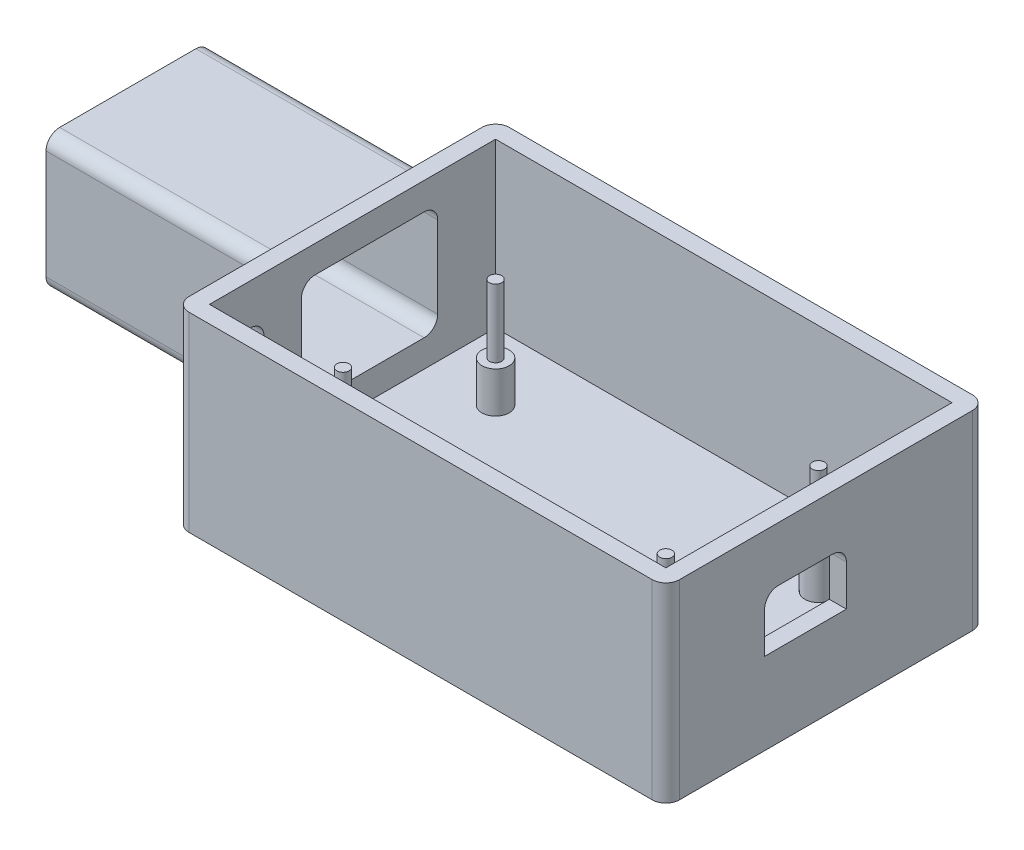
SolidWorks part; units mm, degrees
ref_plane "Front Plane" through (0, 0, 0) normal (0, 0, 1) x (1, 0, 0)
ref_plane "Top Plane" through (0, 0, 0) normal (0, 1, 0) x (1, 0, 0)
ref_plane "Right Plane" through (0, 0, 0) normal (1, 0, 0) x (0, 0, -1)
sketch "Sketch1" plane through (0, 0, 0) normal (0, 1, 0) x (1, 0, 0)
  line L0 (-10.5, -10.5) -> (-10.5, 36.5)
  line L1 (0, 0) -> (51, 0) construction
  line L2 (0, 0) -> (0, 26) construction
  line L3 (0, 26) -> (51, 26) construction
  line L4 (51, 0) -> (51, 26) construction
  line L5 (-10.5, 36.5) -> (61.5, 36.5)
  line L6 (61.5, -10.5) -> (61.5, 36.5)
  line L7 (-10.5, -10.5) -> (61.5, -10.5)
  line L8 (25.5, 36.5) -> (25.5, -10.5) construction
  line L9 (-10.5, 13) -> (61.5, 13) construction
  dimension "D1" = 51
  dimension "D2" = 26
  dimension "D3" = 10.5
extrude "Boss-Extrude1" add sketch "Sketch1" along normal blind 4
sketch "Sketch2" plane through (0, 4, 0) normal (0, 1, 0) x (1, 0, 0)
  line L0 (0, 13) -> (51, 13) construction
  line L1 (25.5, 26) -> (25.5, 0) construction
  line L8 (0, 26) -> (0, 0)
  line L9 (51, 26) -> (0, 26)
  line L10 (51, 0) -> (51, 26)
  line L11 (0, 0) -> (51, 0)
  line L12 (0, 26) -> (0, 0) construction
  line L13 (51, 26) -> (0, 26) construction
  line L14 (51, 0) -> (51, 26) construction
  line L15 (0, 0) -> (51, 0) construction
  circle A4 centre (1.8, 24.2) radius 0.9
  circle A5 centre (1.8, 1.8) radius 0.9
  circle A6 centre (49.2, 1.8) radius 0.9
  circle A7 centre (49.2, 24.2) radius 0.9
  dimension "D2" = 1.8
  dimension "D3" = 1.8
  dimension "D4" = 1.8
  dimension "D1" = 10.5
sketch "Sketch3" plane through (0, 4, 0) normal (0, 1, 0) x (1, 0, 0)
  line L0 (61.5, -10.5) -> (61.5, 36.5) construction
  line L1 (-10.5, -10.5) -> (61.5, -10.5) construction
  line L2 (61.5, 36.5) -> (-10.5, 36.5) construction
  line L3 (-10.5, 36.5) -> (-10.5, -10.5) construction
  line L4 (61.5, -10.5) -> (61.5, 36.5)
  line L5 (-10.5, -10.5) -> (61.5, -10.5)
  line L6 (61.5, 36.5) -> (-10.5, 36.5)
  line L7 (-10.5, 36.5) -> (-10.5, -10.5)
  line L8 (59, -8) -> (59, 34)
  line L9 (59, 34) -> (-8, 34)
  line L10 (-8, 34) -> (-8, -8)
  line L11 (-8, -8) -> (59, -8)
  dimension "D1" = 2.5
extrude "Boss-Extrude3" add sketch "Sketch3" along normal blind 24
extrude "Boss-Extrude4" add sketch "Sketch2" along normal blind 16
sketch "Sketch4" plane through (0, 4, 0) normal (0, 1, 0) x (1, 0, 0)
  line L0 (25.5, 34) -> (25.5, -8) construction
  line L1 (59, 34) -> (-8, 34) construction
  line L2 (-8, -8) -> (59, -8) construction
  line L3 (-8, 13) -> (59, 13) construction
  line L4 (-8, 34) -> (-8, -8) construction
  line L5 (59, -8) -> (59, 34) construction
  circle A0 centre (1.8, 24.2) radius 2
  circle A1 centre (1.8, 1.8) radius 2
  circle A2 centre (49.2, 1.8) radius 2
  circle A3 centre (49.2, 24.2) radius 2
  dimension "D1" = 4
extrude "Boss-Extrude5" add sketch "Sketch4" along normal blind 6
sketch "Sketch5" plane through (61.5, 0, 0) normal (1, 0, 0) x (0, 0, -1)
  line L1 (-8, 28) -> (-8, 4) construction
  line L7 (4, 20) -> (16, 20)
  line L8 (4, 20) -> (4, 12)
  line L9 (4, 12) -> (16, 12)
  line L10 (16, 20) -> (16, 12)
  line L11 (-8, 4) -> (34, 4) construction
  line L12 (-8, 28) -> (-8, 4) construction
  line L13 (-8, 4) -> (34, 4) construction
  dimension "D1" = 8
  dimension "D2" = 12
  dimension "D3" = 8
  dimension "D4" = 12
extrude "Cut-Extrude1" cut sketch "Sketch5" against normal blind 6
fillet "Fillet2" radius 2 4 edges at (-10.5, 14, 10.5) (-10.5, 14, -36.5) (61.5, 14, -36.5) (61.5, 14, 10.5)
fillet "Fillet3" radius 2 2 edges at (60.25, 20, -4) (60.25, 20, -16)
sketch "Sketch6" plane through (0, 0, 10.5) normal (0, 0, 1) x (1, 0, 0)
  line L0 (-8, 4) -> (59, 4) construction
  line L1 (59, 28) -> (59, 4) construction
  line L2 (-8, 4) -> (59, 4) construction
  line L3 (59, 28) -> (59, 4) construction
  line L5 (28, 24) -> (44, 24)
  line L6 (28, 24) -> (28, 15)
  line L7 (28, 15) -> (44, 15)
  line L8 (44, 24) -> (44, 15)
  dimension "D1" = 16
  dimension "D2" = 9
  dimension "D3" = 15
  dimension "D4" = 11
extrude "Cut-Extrude2" [suppressed] cut sketch "Sketch6" against normal blind 6 contours L7 L8 L5 L6
sketch "Sketch8" [suppressed] plane through (-10.5, 0, 0) normal (-1, 0, 0) x (0, 0, 1)
  line L0 (-34.5, 28) -> (-34.5, 0) construction
  line L1 (-22.5, 20) -> (-10.5, 20)
  line L2 (-22.5, 20) -> (-22.5, 12)
  line L3 (-22.5, 12) -> (-10.5, 12)
  line L4 (-10.5, 20) -> (-10.5, 12)
  line L6 (-34, 4) -> (8, 4) construction
  line L7 (-34, 4) -> (8, 4) construction
  dimension "D1" = 12
  dimension "D2" = 8
  dimension "D3" = 8
  dimension "D4" = 12
sketch "Sketch11" plane through (-10.5, 0, 0) normal (-1, 0, 0) x (0, 0, 1)
  line L0 (-34.5, 28) -> (8.5, 28) construction
  line L1 (-27.5, 26) -> (-3.5, 26)
  line L2 (-27.5, 26) -> (-27.5, 6)
  line L3 (-27.5, 6) -> (-3.5, 6)
  line L4 (-3.5, 26) -> (-3.5, 6)
  line L5 (-34.5, 28) -> (-34.5, 0) construction
  dimension "D1" = 24
  dimension "D2" = 20
  dimension "D3" = 2
  dimension "D4" = 7
extrude "Boss-Extrude7" add sketch "Sketch11" along normal blind 33
sketch "Sketch12" plane through (-8, 0, 0) normal (1, 0, 0) x (0, 0, -1)
  line L0 (27.5, 6) -> (3.5, 6) construction
  line L1 (3.5, 26) -> (27.5, 26) construction
  line L2 (3.5, 6) -> (3.5, 26) construction
  line L3 (27.5, 26) -> (27.5, 6) construction
  line L4 (27.5, 6) -> (3.5, 6) construction
  line L5 (3.5, 26) -> (27.5, 26) construction
  line L6 (3.5, 6) -> (3.5, 26) construction
  line L7 (27.5, 26) -> (27.5, 6) construction
  line L8 (5.5, 8) -> (5.5, 24)
  line L9 (5.5, 24) -> (25.5, 24)
  line L10 (25.5, 24) -> (25.5, 8)
  line L11 (25.5, 8) -> (5.5, 8)
  dimension "D1" = 2
extrude "Cut-Extrude4" cut sketch "Sketch12" against normal blind 20 contours L8 L9 L10 L11
sketch "Sketch13" plane through (-43.5, 0, 0) normal (-1, 0, 0) x (0, 0, 1)
  line L0 (-3.5, 26) -> (-27.5, 26) construction
  line L1 (-23, 20.5) -> (-8, 20.5)
  line L2 (-23, 20.5) -> (-23, 11.5)
  line L3 (-23, 11.5) -> (-8, 11.5)
  line L4 (-8, 20.5) -> (-8, 11.5)
  line L7 (-3.5, 6) -> (-3.5, 26) construction
  dimension "D1" = 15
  dimension "D2" = 9
  dimension "D3" = 5.5
  dimension "D4" = 4.5
extrude "Cut-Extrude5" cut sketch "Sketch13" against normal blind 20
fillet "Fillet4" radius 2 4 edges at (-18, 8, -25.5) (-18, 24, -25.5) (-18, 24, -5.5) (-18, 8, -5.5)
fillet "Fillet5" radius 2 4 edges at (-27, 6, -3.5) (-27, 26, -3.5) (-27, 6, -27.5) (-27, 26, -27.5)
sketch "Sketch14" plane through (-10.5, 0, 0) normal (-1, 0, 0) x (0, 0, 1)
  line L0 (-34.5, 0) -> (8.5, 0) construction
  line L1 (0, 22) -> (6, 22)
  line L2 (0, 22) -> (0, 8)
  line L3 (0, 8) -> (6, 8)
  line L4 (6, 22) -> (6, 8)
  dimension "D1" = 6
  dimension "D2" = 14
  dimension "D3" = 8
extrude "Cut-Extrude6" cut sketch "Sketch14" against normal blind 5
fillet "Fillet6" radius 2 4 edges at (-9.25, 22, 6) (-9.25, 22, 0) (-9.25, 8, 6) (-9.25, 8, 0)
